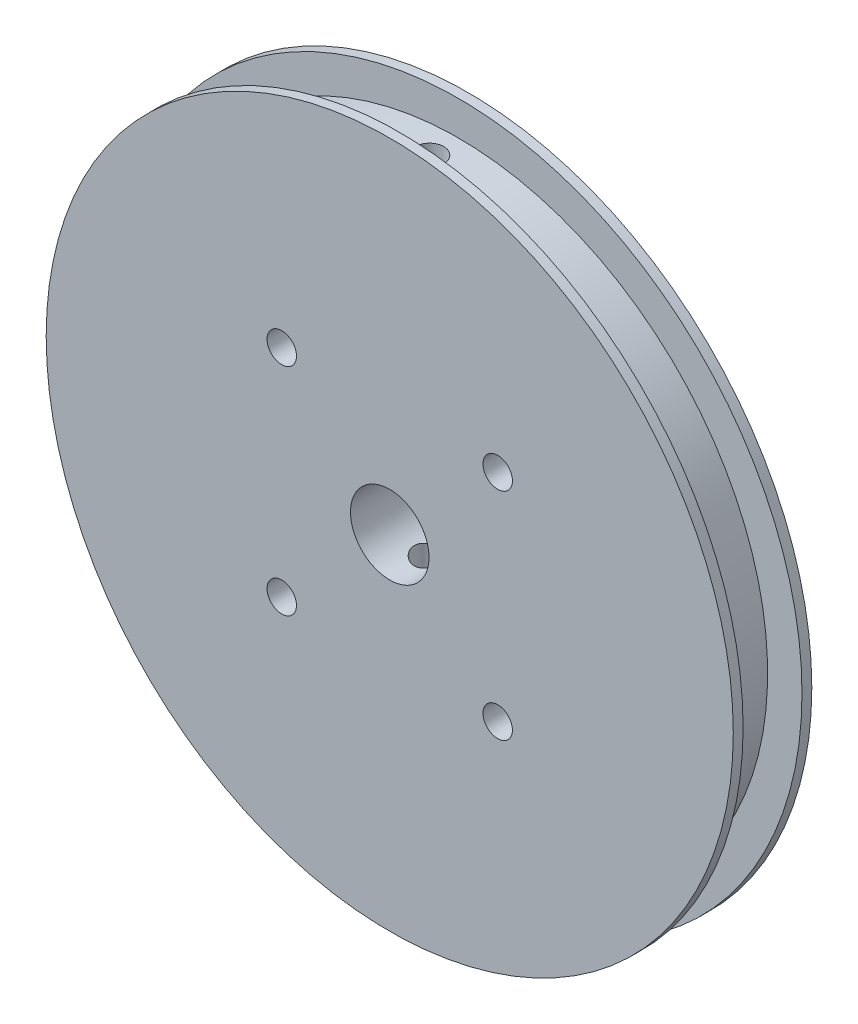
SolidWorks part; units mm, degrees
material "Acrylic (Medium-high impact)"
ref_plane "Front Plane" through (0, 0, 0) normal (0, 0, 1) x (1, 0, 0)
ref_plane "Top Plane" through (0, 0, 0) normal (0, 1, 0) x (1, 0, 0)
ref_plane "Right Plane" through (0, 0, 0) normal (1, 0, 0) x (0, 0, -1)
sketch "Sketch1" plane through (0, 0, 0) normal (0, 0, 1) x (1, 0, 0)
  circle A0 centre (0, 0) radius 35
  dimension "D1" = 70
extrude "Pulley Boss-Extrude1" add sketch "Sketch1" along normal blind 8
sketch "Sketch2" plane through (0, 0, 0) normal (0, 1, 0) x (1, 0, 0)
  line L0 (35, -8) -> (35, 0) construction
  line L1 (35, -1) -> (31.5, -1)
  line L2 (35, -1) -> (35, -7)
  line L3 (35, -7) -> (31.5, -7)
  line L4 (31.5, -1) -> (31.5, 0) construction
  line L5 (0, 14.6216) -> (0, -23.6188) construction
  line L6 (31.5, -1) -> (31.5, -7)
  line L7 (35, 0) -> (-35, 0) construction
  line L10 (31.5, -7) -> (31.5, -8) construction
  line L11 (-35, -8) -> (35, -8) construction
  dimension "D1" = 6
  dimension "D2" = 3.5
  dimension "D3" = 31.5
revolve "Belt Cut-Revolve3" cut sketch "Sketch2" angle 360 about L5
sketch "Sketch3" plane through (0, 0, 0) normal (0, 0, 1) x (1, 0, 0)
  circle A0 centre (0, 0) radius 4
  dimension "D1" = 8
extrude "Shaft Cut-Extrude1" cut sketch "Sketch3" along normal up to surface (8 mm away) up to face at (35, 0, 8)
sketch "Sketch4" plane through (0, 0, 0) normal (0, 1, 0) x (1, 0, 0)
  line L0 (0, 0) -> (0, -4) construction
  line L1 (0, -4) -> (0, -8) construction
  line L2 (-35, -8) -> (35, -8) construction
  circle A0 centre (0, -4) radius 1.5
  dimension "D1" = 3
extrude "Sprint Hole Cut-Extrude2" cut sketch "Sketch4" against normal up to surface and the other way up to surface up to face at (-31.5, 0, 7) other way up to face at (-31.5, 0, 7)
sketch "Sketch5" plane through (0, 0, 8) normal (0, 0, 1) x (1, 0, 0)
  line L0 (-11, 11) -> (0, 0) construction
  line L1 (-11, 11) -> (11, 11) construction
  line L2 (-11, 11) -> (-11, -11) construction
  line L3 (-11, -11) -> (11, -11) construction
  line L4 (11, 11) -> (11, -11) construction
  line L5 (11, 11) -> (0, 0) construction
  line L6 (11, -11) -> (0, 0) construction
  line L7 (0, 0) -> (-11, -11) construction
  circle A0 centre (0, 0) radius 20 construction
  circle A1 centre (0, 0) radius 8 construction
  circle A2 centre (11, 11) radius 1.5
  circle A3 centre (-11, 11) radius 1.5
  circle A4 centre (-11, -11) radius 1.5
  circle A5 centre (11, -11) radius 1.5
  dimension "D1" = 40
  dimension "D3" = 16
  dimension "D4" = 3
  dimension "D2" = 22
extrude "Arm Distans Mounting Holes Cut-Extrude1" cut sketch "Sketch5" against normal up to surface (8 mm away) up to face at (35, 0, 0)
